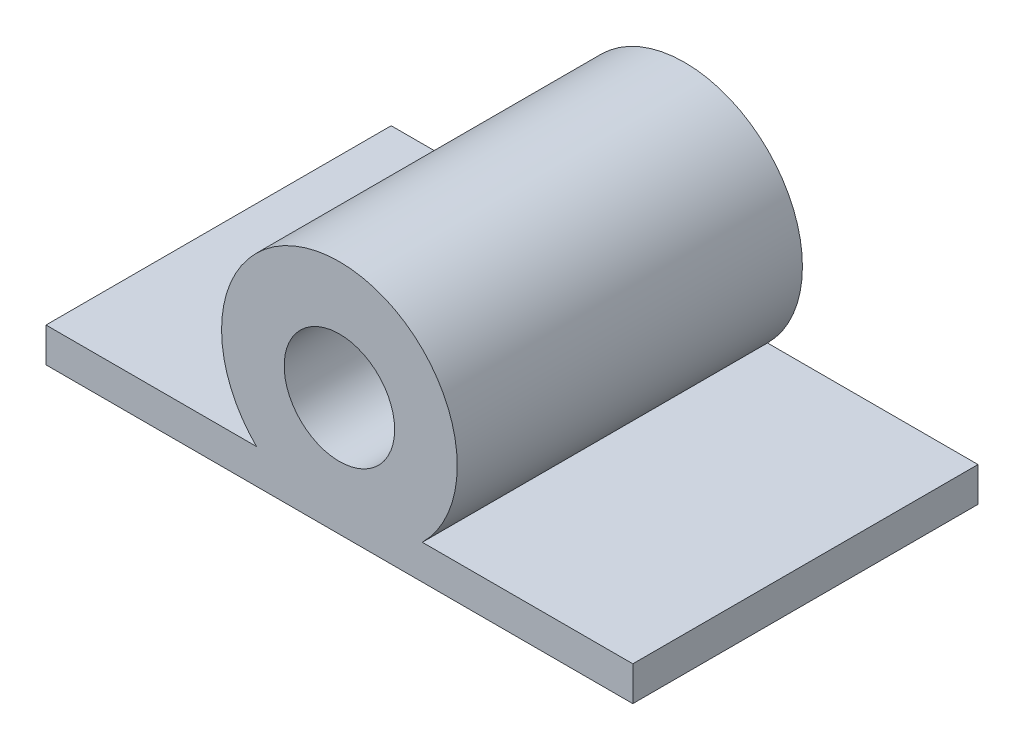
SolidWorks part; units mm, degrees
ref_plane "Front Plane" through (0, 0, 0) normal (0, 0, 1) x (1, 0, 0)
ref_plane "Top Plane" through (0, 0, 0) normal (0, 1, 0) x (1, 0, 0)
ref_plane "Right Plane" through (0, 0, 0) normal (1, 0, 0) x (0, 0, -1)
sketch "Sketch2" plane through (0, 0, 0) normal (0, 1, 0) x (1, 0, 0)
  line L1 (0, 0) -> (85, 0)
  line L2 (0, 0) -> (0, 50)
  line L3 (0, 50) -> (85, 50)
  line L4 (85, 0) -> (85, 50)
  dimension "D1" = 85
  dimension "D2" = 50
extrude "Boss-Extrude2" add sketch "Sketch2" along normal blind 5
sketch "Sketch3" plane through (0, 0, 0) normal (0, 0, 1) x (1, 0, 0)
  line L0 (42.5, 5) -> (42.5, 17.1316) construction
  line L1 (0, 5) -> (85, 5) construction
  line L2 (42.5, 17.1316) -> (50.5, 17.1316) construction
  circle A0 centre (42.5, 17.1316) radius 8
  circle A1 centre (42.5, 17.1316) radius 17.0688
  dimension "D1" = 8
extrude "Boss-Extrude4" add sketch "Sketch3" against normal blind 50
ref_plane "Plane15" through (0, 5, -50) normal (0, 0, 1) x (1, 0, 0)
sketch "Sketch5" plane through (0, 5, 0) normal (0, 1, 0) x (1, 0, 0)
  line L0 (11.6653, 36.1704) -> (13.1653, 36.1704) construction
  circle A0 centre (11.6653, 36.1704) radius 1.5
  point P2 (0, 0)
  dimension "D1" = 1.5
extrude "Cut-Extrude1" cut sketch "Sketch5" against normal blind 50
